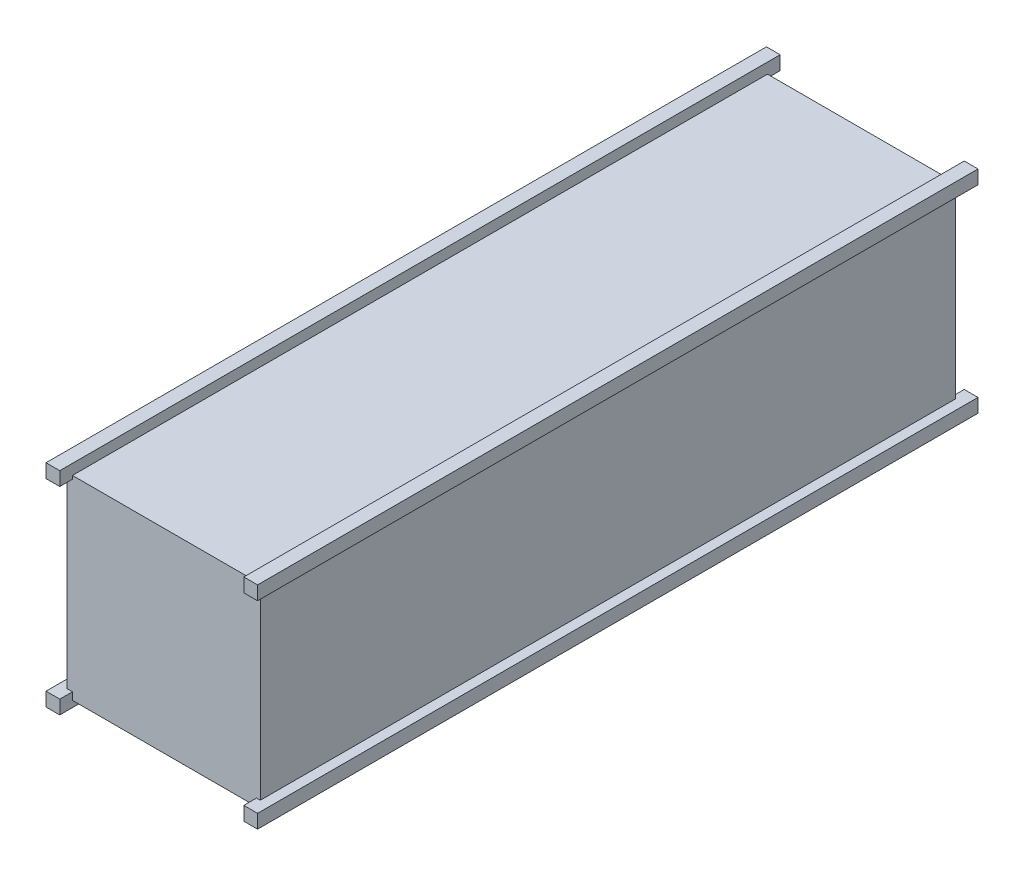
SolidWorks part; units mm, degrees
ref_plane "Front Plane" through (0, 0, 0) normal (0, 0, 1) x (1, 0, 0)
ref_plane "Top Plane" through (0, 0, 0) normal (0, 1, 0) x (1, 0, 0)
ref_plane "Right Plane" through (0, 0, 0) normal (1, 0, 0) x (0, 0, -1)
sketch "Sketch1" plane through (0, 0, 0) normal (0, 0, 1) x (1, 0, 0)
  line L1 (0, 0) -> (100, 0)
  line L2 (0, 0) -> (0, 100)
  line L3 (0, 100) -> (100, 100)
  line L4 (100, 0) -> (100, 100)
  line L5 (0, 100) -> (6.5, 100)
  line L6 (0, 100) -> (0, 93.5)
  line L7 (0, 93.5) -> (6.5, 93.5)
  line L8 (6.5, 100) -> (6.5, 93.5)
  line L9 (100, 100) -> (93.5, 100)
  line L10 (100, 100) -> (100, 93.5)
  line L11 (100, 93.5) -> (93.5, 93.5)
  line L12 (93.5, 100) -> (93.5, 93.5)
  line L13 (100, 0) -> (93.5, 0)
  line L14 (100, 0) -> (100, 6.5)
  line L15 (100, 6.5) -> (93.5, 6.5)
  line L16 (93.5, 0) -> (93.5, 6.5)
  line L17 (0, 0) -> (6.5, 0)
  line L18 (0, 0) -> (0, 6.5)
  line L19 (0, 6.5) -> (6.5, 6.5)
  line L20 (6.5, 0) -> (6.5, 6.5)
  dimension "D1" = 100
  dimension "D2" = 100
  dimension "D3" = 6.5
  dimension "D4" = 6.5
  dimension "D5" = 6.5
  dimension "D6" = 6.5
  dimension "D7" = 6.5
  dimension "D8" = 6.5
  dimension "D9" = 6.5
  dimension "D10" = 6.5
extrude "Boss-Extrude1" add sketch "Sketch1" against normal blind 340.5 contours L8 L3 L2 L7 | L3 L12 L11 L4 | L16 L1 L4 L15 | L1 L20 L19 L2
ref_plane "Plane1" through (0, 0, -6) normal (0, 0, -1) x (-1, 0, 0)
sketch "Sketch2" plane through (0, 0, -6) normal (0, 0, -1) x (-1, 0, 0)
  line L1 (-95.3068, 95.0524) -> (-4.0009, 95.0524)
  line L2 (-95.3068, 95.0524) -> (-95.3068, 2.9836)
  line L3 (-95.3068, 2.9836) -> (-4.0009, 2.9836)
  line L4 (-4.0009, 95.0524) -> (-4.0009, 2.9836)
extrude "Boss-Extrude2" add sketch "Sketch2" along normal blind 328.5
